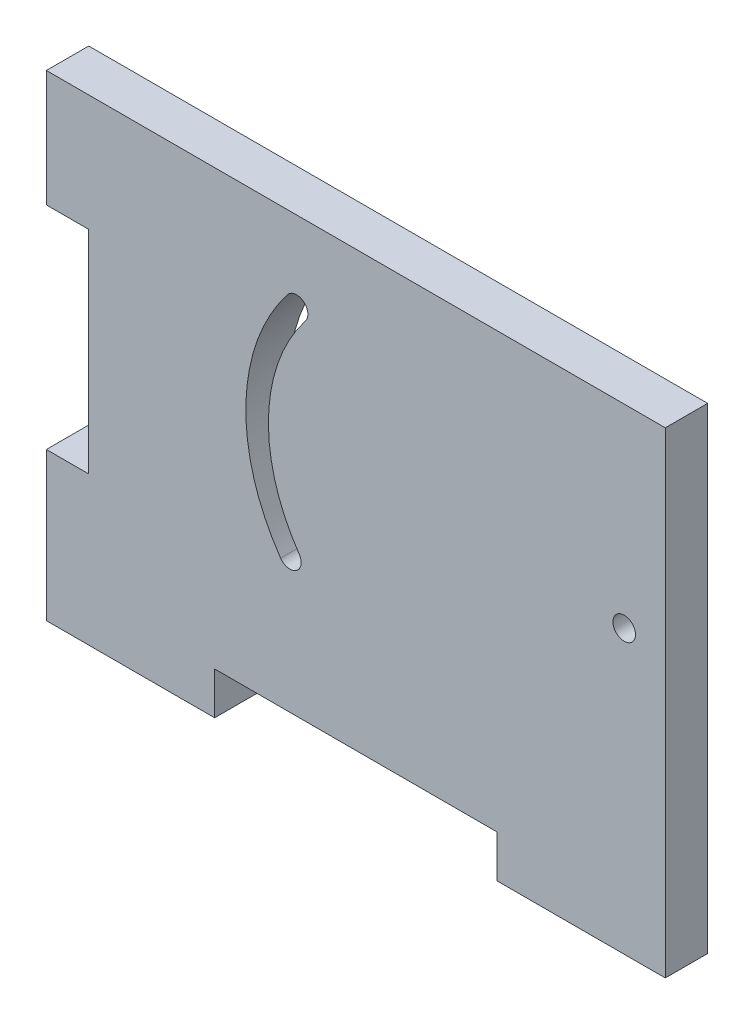
SolidWorks part; units mm, degrees
ref_plane "Front Plane" through (0, 0, 0) normal (0, 0, 1) x (1, 0, 0)
ref_plane "Top Plane" through (0, 0, 0) normal (0, 1, 0) x (1, 0, 0)
ref_plane "Right Plane" through (0, 0, 0) normal (1, 0, 0) x (0, 0, -1)
sketch "Sketch1" plane through (0, 0, 0) normal (0, 0, 1) x (1, 0, 0)
  line L4 (-25.2982, 6) -> (-25.2982, -6) construction
  line L6 (-55.8559, -40) -> (31.8193, -40)
  line L7 (-55.8559, -40) -> (-55.8559, 27.4983)
  line L8 (-55.8559, 27.4983) -> (31.8193, 27.4983)
  line L9 (31.8193, -40) -> (31.8193, 27.4983)
  line L10 (-55.8559, -40) -> (31.8193, 27.4983) construction
  line L11 (-55.8559, 27.4983) -> (31.8193, -40) construction
  line L12 (-32.0183, -40) -> (7.9817, -40)
  line L13 (-32.0183, -40) -> (-32.0183, -34)
  line L14 (-32.0183, -34) -> (7.9817, -34)
  line L15 (7.9817, -40) -> (7.9817, -34)
  line L16 (-55.8559, -19) -> (-49.8559, -19)
  line L17 (-55.8559, -19) -> (-55.8559, 11)
  line L18 (-55.8559, 11) -> (-49.8559, 11)
  line L19 (-49.8559, -19) -> (-49.8559, 11)
  circle A0 centre (0, 0) radius 26 construction
  circle A1 centre (26, 0) radius 1.6
  circle A2 centre (-25.2982, 6) radius 1.6
  circle A3 centre (-25.2982, -6) radius 1.6
  arc A4 (-21.3571, -14.8282) -> (-20.4114, 16.1051) centre (0, 0) cw construction
  arc A5 (-21.6675, 17.0961) -> (-22.6713, -15.7407) centre (0, 0) ccw
  arc A6 (-19.1554, 15.114) -> (-20.0428, -13.9157) centre (0, 0) ccw
  arc A7 (-19.1554, 15.114) -> (-21.6675, 17.0961) centre (-20.4114, 16.1051) ccw
  arc A8 (-22.6713, -15.7407) -> (-20.0428, -13.9157) centre (-21.3571, -14.8282) ccw
  point P0 (-12.0183, -6.2508)
  point P15 (-25.9879, 0.7944)
  point P20 (-12.0183, -34)
  point P29 (-49.8559, -4)
  dimension "D1" = 52
  dimension "D2" = 3.2
  dimension "D5" = 40
  dimension "D3" = 40
  dimension "D4" = 12
  dimension "D6" = 6
  dimension "D7" = 6
  dimension "D8" = 30
  dimension "D9" = 30
  dimension "D10" = 87.6752
  dimension "D11" = 67.4983
extrude "Boss-Extrude1" add sketch "Sketch1" along normal blind 6 contours L6 L9 L8 L7 A8 A5 A7 A6 A1
